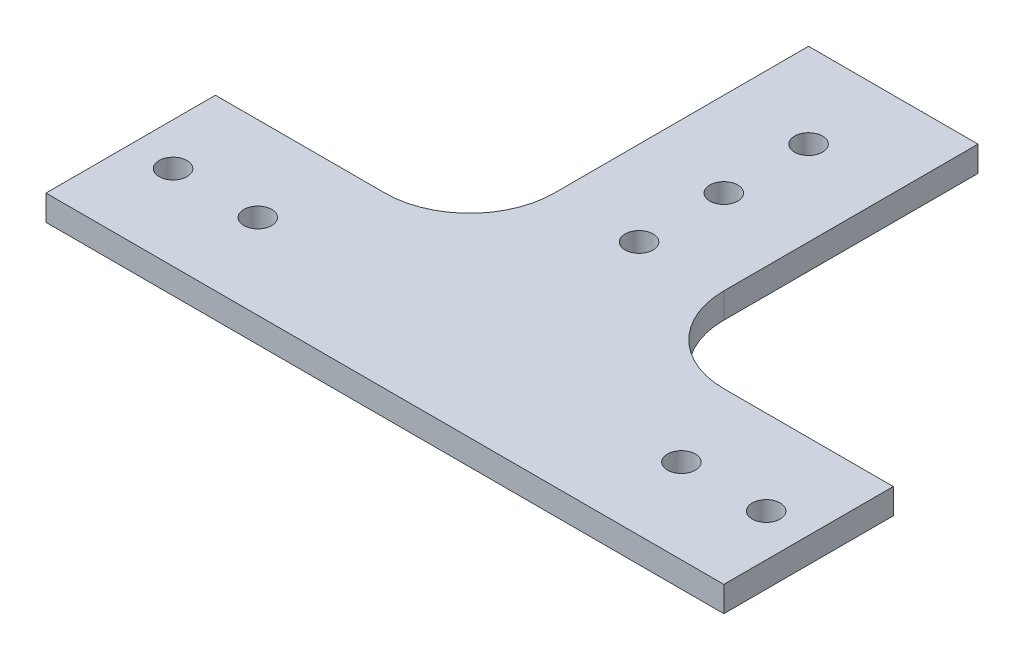
SolidWorks part; units mm, degrees
ref_plane "前视基准面" through (0, 0, 0) normal (0, 0, 1) x (1, 0, 0)
ref_plane "上视基准面" through (0, 0, 0) normal (0, 1, 0) x (1, 0, 0)
ref_plane "右视基准面" through (0, 0, 0) normal (1, 0, 0) x (0, 0, -1)
other "Configuration Table"
sketch "草图1" plane through (0, 0, 0) normal (0, 1, 0) x (1, 0, 0)
  line L0 (-40.3341, -30.3341) -> (39.6659, -30.3341)
  line L1 (39.6659, -30.3341) -> (39.6659, -10.3341)
  line L2 (39.6659, -10.3341) -> (9.6659, -10.3341)
  line L3 (9.6659, -10.3341) -> (9.6659, 29.6659)
  line L4 (9.6659, 29.6659) -> (-10.3341, 29.6659)
  line L5 (-10.3341, 29.6659) -> (-10.3341, -10.3341)
  line L6 (-10.3341, -10.3341) -> (-40.3341, -10.3341)
  line L7 (-40.3341, -10.3341) -> (-40.3341, -30.3341)
  circle A0 centre (-0.3341, -0.3341) radius 1.65
  circle A1 centre (-0.3341, 9.6659) radius 1.65
  circle A2 centre (-0.3341, 19.6659) radius 1.65
  circle A3 centre (-25.3341, -20.3341) radius 1.65
  circle A4 centre (-35.3341, -20.3341) radius 1.65
  circle A5 centre (24.6659, -20.3341) radius 1.65
  circle A6 centre (34.6659, -20.3341) radius 1.65
  dimension "D1" = 3.3
extrude "凸台-拉伸1" add sketch "草图1" along normal blind 3
fillet "圆角1" radius 10 2 edges at (-10.3341, 1.5, 10.3341) (9.6659, 1.5, 10.3341)
